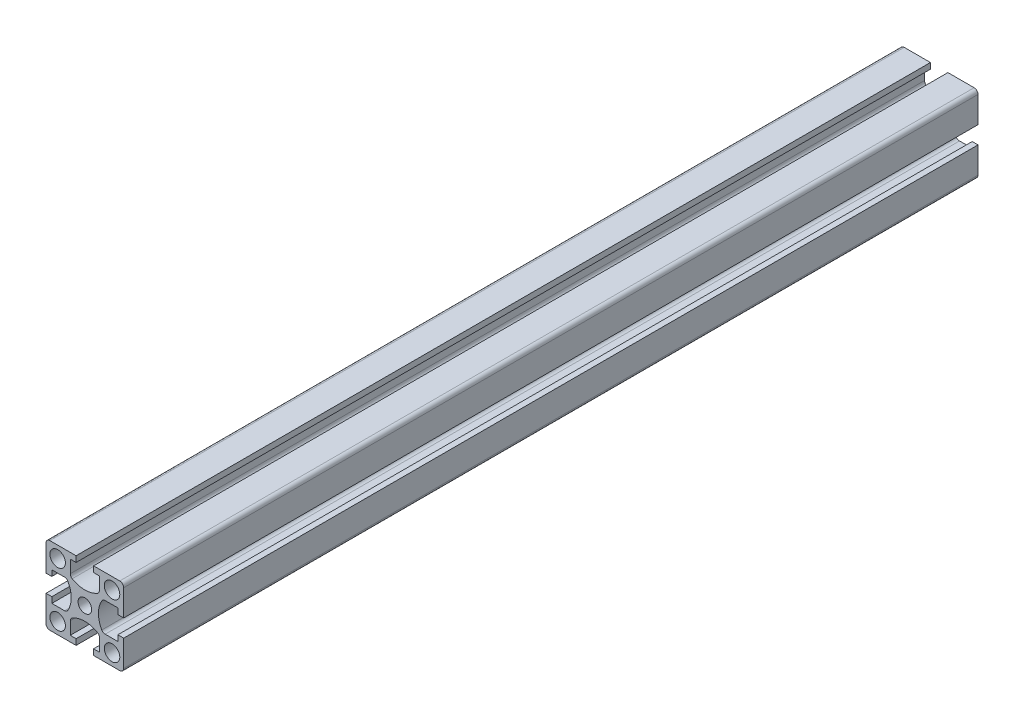
SolidWorks part; units mm, degrees
ref_plane "Front Plane" through (0, 0, 0) normal (0, 0, 1) x (1, 0, 0)
ref_plane "Top Plane" through (0, 0, 0) normal (0, 1, 0) x (1, 0, 0)
ref_plane "Right Plane" through (0, 0, 0) normal (1, 0, 0) x (0, 0, -1)
sketch "Sketch1" plane through (0, 0, 0) normal (0, 0, 1) x (1, 0, 0)
  line L64 (-12.5, 11.25) -> (-12.5, 2.8125)
  line L65 (-12.5, 2.8125) -> (-10.625, 2.8125)
  line L66 (-10.625, 2.8125) -> (-10.625, 4.6875)
  line L67 (-10.625, 4.6875) -> (-6.5461, 4.6875)
  line L68 (-6.5461, -4.6875) -> (-10.625, -4.6875)
  line L69 (-10.625, -4.6875) -> (-10.625, -2.8125)
  line L70 (-10.625, -2.8125) -> (-12.5, -2.8125)
  line L71 (-12.5, -2.8125) -> (-12.5, -11.25)
  line L72 (-11.25, -12.5) -> (-2.8125, -12.5)
  line L73 (-2.8125, -12.5) -> (-2.8125, -10.625)
  line L74 (-2.8125, -10.625) -> (-4.6875, -10.625)
  line L75 (-4.6875, -10.625) -> (-4.6875, -6.5461)
  line L76 (4.6875, -6.5461) -> (4.6875, -10.625)
  line L77 (4.6875, -10.625) -> (2.8125, -10.625)
  line L78 (2.8125, -10.625) -> (2.8125, -12.5)
  line L79 (2.8125, -12.5) -> (11.25, -12.5)
  line L80 (12.5, -11.25) -> (12.5, -2.8125)
  line L81 (12.5, -2.8125) -> (10.625, -2.8125)
  line L82 (10.625, -2.8125) -> (10.625, -4.6875)
  line L83 (10.625, -4.6875) -> (6.5461, -4.6875)
  line L84 (6.5461, 4.6875) -> (10.625, 4.6875)
  line L85 (10.625, 4.6875) -> (10.625, 2.8125)
  line L86 (10.625, 2.8125) -> (12.5, 2.8125)
  line L87 (12.5, 2.8125) -> (12.5, 11.25)
  line L88 (11.25, 12.5) -> (2.8125, 12.5)
  line L89 (2.8125, 12.5) -> (2.8125, 10.625)
  line L90 (2.8125, 10.625) -> (4.6875, 10.625)
  line L91 (4.6875, 10.625) -> (4.6875, 6.5461)
  line L92 (-4.6875, 6.5461) -> (-4.6875, 10.625)
  line L93 (-4.6875, 10.625) -> (-2.8125, 10.625)
  line L94 (-2.8125, 10.625) -> (-2.8125, 12.5)
  line L95 (-2.8125, 12.5) -> (-11.25, 12.5)
  circle A5 centre (-8.75, -8.75) radius 2.5
  circle A6 centre (8.75, -8.75) radius 2.5
  circle A7 centre (8.75, 8.75) radius 2.5
  circle A8 centre (0, 0) radius 2.1875
  circle A9 centre (-8.75, 8.75) radius 2.5
  arc A32 (-11.25, 12.5) -> (-12.5, 11.25) centre (-11.25, 11.25) ccw
  arc A33 (-5.4635, 4.0625) -> (-6.5461, 4.6875) centre (-6.5461, 3.4375) ccw
  arc A34 (-5.4635, -4.0625) -> (-5.4635, 4.0625) centre (-12.5, 0) ccw
  arc A35 (-6.5461, -4.6875) -> (-5.4635, -4.0625) centre (-6.5461, -3.4375) ccw
  arc A36 (-12.5, -11.25) -> (-11.25, -12.5) centre (-11.25, -11.25) ccw
  arc A37 (-4.0625, -5.4635) -> (-4.6875, -6.5461) centre (-3.4375, -6.5461) ccw
  arc A38 (4.0625, -5.4635) -> (-4.0625, -5.4635) centre (0, -12.5) ccw
  arc A39 (4.6875, -6.5461) -> (4.0625, -5.4635) centre (3.4375, -6.5461) ccw
  arc A40 (11.25, -12.5) -> (12.5, -11.25) centre (11.25, -11.25) ccw
  arc A41 (5.4635, -4.0625) -> (6.5461, -4.6875) centre (6.5461, -3.4375) ccw
  arc A42 (5.4635, 4.0625) -> (5.4635, -4.0625) centre (12.5, 0) ccw
  arc A43 (6.5461, 4.6875) -> (5.4635, 4.0625) centre (6.5461, 3.4375) ccw
  arc A44 (12.5, 11.25) -> (11.25, 12.5) centre (11.25, 11.25) ccw
  arc A45 (4.0625, 5.4635) -> (4.6875, 6.5461) centre (3.4375, 6.5461) ccw
  arc A46 (-4.0625, 5.4635) -> (4.0625, 5.4635) centre (0, 12.5) ccw
  arc A47 (-4.6875, 6.5461) -> (-4.0625, 5.4635) centre (-3.4375, 6.5461) ccw
extrude "Boss-Extrude1" add sketch "Sketch1" along normal blind 275
